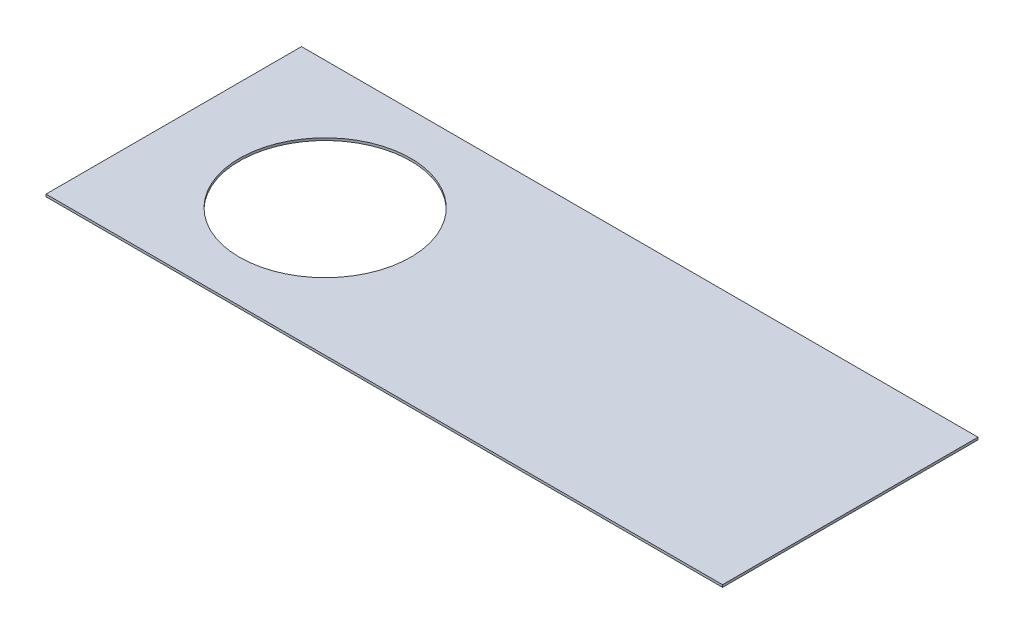
SolidWorks part; units mm, degrees
ref_plane "Front Plane" through (0, 0, 0) normal (0, 0, 1) x (1, 0, 0)
ref_plane "Top Plane" through (0, 0, 0) normal (0, 1, 0) x (1, 0, 0)
ref_plane "Right Plane" through (0, 0, 0) normal (1, 0, 0) x (0, 0, -1)
sketch "Sketch1" plane through (0, 0, 0) normal (0, 1, 0) x (1, 0, 0)
  line L1 (0, 0) -> (454.025, 0)
  line L2 (0, 0) -> (0, 171.45)
  line L3 (0, 171.45) -> (454.025, 171.45)
  line L4 (454.025, 0) -> (454.025, 171.45)
  dimension "D1" = 171.45
  dimension "D2" = 454.025
extrude "Boss-Extrude1" add sketch "Sketch1" along normal blind 1.5875
sketch "Sketch7" plane through (0, 1.5875, 0) normal (0, 1, 0) x (1, 0, 0)
  line L1 (0, 171.45) -> (0, 0) construction
  circle A0 centre (101.6, 85.725) radius 57.5
  point P6 (0, 85.725)
  dimension "D2" = 115
  dimension "D1" = 101.6
extrude "Cut-Extrude4" cut sketch "Sketch7" against normal through all
